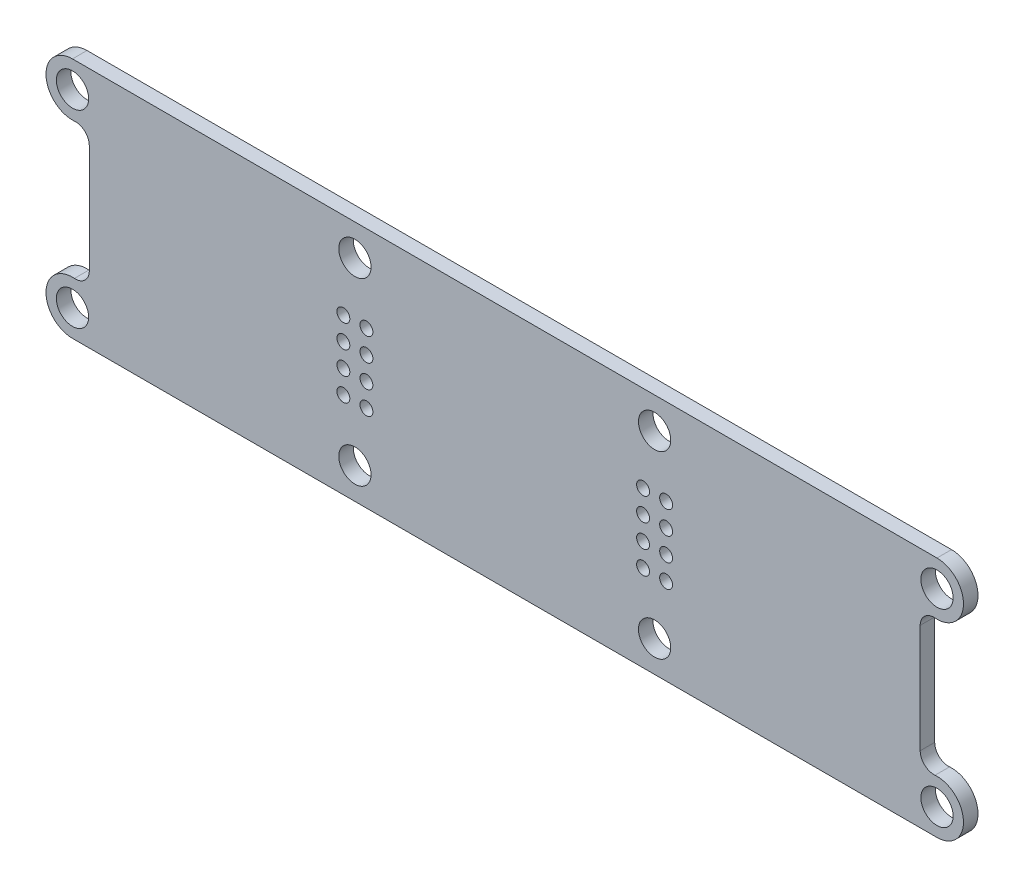
SolidWorks part; units mm, degrees
ref_plane "Front Plane" through (0, 0, 0) normal (0, 0, 1) x (1, 0, 0)
ref_plane "Top Plane" through (0, 0, 0) normal (0, 1, 0) x (1, 0, 0)
ref_plane "Right Plane" through (0, 0, 0) normal (1, 0, 0) x (0, 0, -1)
sketch "Sketch1" plane through (0, 0, -38.7925) normal (0, 0, -1) x (-1, 0, 0)
  line L72 (23.8125, 6.6675) -> (-23.8125, 6.6675)
  line L74 (-23.8125, -6.6675) -> (23.8125, -6.6675)
  line L75 (22.887, -2.9905) -> (22.887, 2.9905)
  line L76 (23.8125, 6.6675) -> (-23.8125, 6.6675)
  line L78 (-23.8125, -6.6675) -> (23.8125, -6.6675)
  line L152 (-22.887, 2.9905) -> (-22.887, -2.9905)
  line L153 (-22.887, 2.9905) -> (-22.887, -2.9905)
  line L164 (22.887, -2.9905) -> (22.887, 2.9905)
  arc A78 (23.7051, 3.7505) -> (23.8125, 6.6675) centre (23.8125, 5.207) ccw
  arc A79 (-23.8125, 6.6675) -> (-23.7051, 3.7505) centre (-23.8125, 5.207) ccw
  arc A80 (-23.7051, -3.7505) -> (-23.8125, -6.6675) centre (-23.8125, -5.207) ccw
  arc A81 (23.8125, -6.6675) -> (23.7051, -3.7505) centre (23.8125, -5.207) ccw
  arc A82 (23.7051, 3.7505) -> (23.8125, 6.6675) centre (23.8125, 5.207) ccw
  arc A83 (-23.8125, 6.6675) -> (-23.7051, 3.7505) centre (-23.8125, 5.207) ccw
  arc A84 (-23.7051, -3.7505) -> (-23.8125, -6.6675) centre (-23.8125, -5.207) ccw
  arc A85 (23.8125, -6.6675) -> (23.7051, -3.7505) centre (23.8125, -5.207) ccw
  arc A173 (-22.887, 2.9905) -> (-23.7051, 3.7505) centre (-23.649, 2.9905) ccw
  arc A174 (-22.887, 2.9905) -> (-23.7051, 3.7505) centre (-23.649, 2.9905) ccw
  arc A175 (-23.7051, -3.7505) -> (-22.887, -2.9905) centre (-23.649, -2.9905) ccw
  arc A176 (-23.7051, -3.7505) -> (-22.887, -2.9905) centre (-23.649, -2.9905) ccw
  arc A195 (23.7051, 3.7505) -> (22.887, 2.9905) centre (23.649, 2.9905) ccw
  arc A196 (23.7051, 3.7505) -> (22.887, 2.9905) centre (23.649, 2.9905) ccw
  arc A197 (22.887, -2.9905) -> (23.7051, -3.7505) centre (23.649, -2.9905) ccw
  arc A198 (22.887, -2.9905) -> (23.7051, -3.7505) centre (23.649, -2.9905) ccw
  dimension "D1" = 0.127
extrude "Boss-Extrude1" add sketch "Sketch1" along normal blind 0.8
sketch "Sketch2" plane through (0, 0, -39.5925) normal (0, 0, -1) x (-1, 0, 0)
  circle A13 centre (-7.62, -1.905) radius 0.3556
  circle A17 centre (-7.62, -1.905) radius 0.3556
  circle A23 centre (-8.89, -1.905) radius 0.3556
  circle A37 centre (-8.89, -1.905) radius 0.3556
  circle A39 centre (-7.62, 1.905) radius 0.3556
  circle A41 centre (-7.62, 1.905) radius 0.3556
  circle A43 centre (-8.89, 1.905) radius 0.3556
  circle A45 centre (-8.89, 1.905) radius 0.3556
  circle A47 centre (-7.62, 0.635) radius 0.3556
  circle A49 centre (-7.62, 0.635) radius 0.3556
  circle A51 centre (-8.89, 0.635) radius 0.3556
  circle A53 centre (-8.89, 0.635) radius 0.3556
  circle A55 centre (-7.62, -0.635) radius 0.3556
  circle A226 centre (-7.62, -0.635) radius 0.3556
  circle A227 centre (-8.89, -0.635) radius 0.3556
  circle A228 centre (-8.89, -0.635) radius 0.3556
  circle A247 centre (8.89, 1.905) radius 0.3556
  circle A248 centre (8.89, 1.905) radius 0.3556
  circle A249 centre (7.62, 1.905) radius 0.3556
  circle A250 centre (7.62, 1.905) radius 0.3556
  circle A263 centre (8.89, -1.905) radius 0.3556
  circle A264 centre (8.89, -1.905) radius 0.3556
  circle A265 centre (7.62, -1.905) radius 0.3556
  circle A266 centre (7.62, -1.905) radius 0.3556
  circle A267 centre (8.89, -0.635) radius 0.3556
  circle A268 centre (8.89, -0.635) radius 0.3556
  circle A269 centre (7.62, -0.635) radius 0.3556
  circle A270 centre (7.62, -0.635) radius 0.3556
  circle A271 centre (8.89, 0.635) radius 0.3556
  circle A272 centre (8.89, 0.635) radius 0.3556
  circle A273 centre (7.62, 0.635) radius 0.3556
  circle A274 centre (7.62, 0.635) radius 0.3556
  dimension "D5" = 0
  dimension "D9" = 0
  dimension "D10" = 0
  dimension "D11" = 0
  dimension "D12" = 0
  dimension "D19" = 0
  dimension "D20" = 0
  dimension "D21" = 0
  dimension "D31" = 0
  dimension "D32" = 0
  dimension "D39" = 0
  dimension "D40" = 0
  dimension "D41" = 0
  dimension "D42" = 0
  dimension "D43" = 0
  dimension "D44" = 0
extrude "Cut-Extrude1" cut sketch "Sketch2" against normal through all
sketch "Sketch3" plane through (0, 0, -39.5925) normal (0, 0, -1) x (-1, 0, 0)
  circle A0 centre (-23.8125, 5.207) radius 0.889
  circle A1 centre (-23.8125, -5.207) radius 0.889
  circle A2 centre (23.8125, 5.207) radius 0.889
  circle A3 centre (23.8125, -5.207) radius 0.889
  circle A4 centre (-8.255, 4.953) radius 0.889
  circle A5 centre (8.255, 4.953) radius 0.889
  circle A6 centre (8.255, -4.953) radius 0.889
  circle A7 centre (-8.255, -4.953) radius 0.889
  dimension "D1" = 1.778
  dimension "D2" = 47.625
  dimension "D3" = 10.414
extrude "Cut-Extrude2" cut sketch "Sketch3" against normal through all both and the other way through all
sketch "Sketch4" plane through (0, 0, -39.5925) normal (0, 0, -1) x (-1, 0, 0)
  line L0 (-23.8125, -6.6675) -> (-23.8125, -5.207) construction
  line L1 (-23.8125, -5.207) -> (-23.7051, -3.7505) construction
  line L2 (-23.7051, -3.7505) -> (-23.649, -2.9905) construction
  line L3 (-23.649, -2.9905) -> (-22.887, -2.9905) construction
  line L4 (-22.887, 2.9905) -> (-22.887, -2.9905)
  line L5 (-23.8125, -6.6675) -> (23.8125, -6.6675)
  line L6 (22.887, -2.9905) -> (22.887, 2.9905)
  line L7 (23.8125, 6.6675) -> (-23.8125, 6.6675)
  line L8 (-22.887, 2.9905) -> (-22.887, -2.9905)
  line L9 (-23.8125, -6.6675) -> (23.8125, -6.6675)
  line L10 (22.887, -2.9905) -> (22.887, 2.9905)
  line L11 (23.8125, 6.6675) -> (-23.8125, 6.6675)
  arc A8 (-22.887, 2.9905) -> (-23.7051, 3.7505) centre (-23.649, 2.9905) ccw
  arc A9 (-23.7051, -3.7505) -> (-22.887, -2.9905) centre (-23.649, -2.9905) ccw
  arc A10 (-23.7051, -3.7505) -> (-23.8125, -6.6675) centre (-23.8125, -5.207) ccw
  arc A11 (23.8125, -6.6675) -> (23.7051, -3.7505) centre (23.8125, -5.207) ccw
  arc A12 (22.887, -2.9905) -> (23.7051, -3.7505) centre (23.649, -2.9905) ccw
  arc A13 (23.7051, 3.7505) -> (22.887, 2.9905) centre (23.649, 2.9905) ccw
  arc A14 (23.7051, 3.7505) -> (23.8125, 6.6675) centre (23.8125, 5.207) ccw
  arc A15 (-23.8125, 6.6675) -> (-23.7051, 3.7505) centre (-23.8125, 5.207) ccw
  arc A16 (-22.887, 2.9905) -> (-23.7051, 3.7505) centre (-23.649, 2.9905) ccw
  arc A17 (-23.7051, -3.7505) -> (-22.887, -2.9905) centre (-23.649, -2.9905) ccw
  arc A18 (-23.7051, -3.7505) -> (-23.8125, -6.6675) centre (-23.8125, -5.207) ccw
  arc A19 (23.8125, -6.6675) -> (23.7051, -3.7505) centre (23.8125, -5.207) ccw
  arc A20 (22.887, -2.9905) -> (23.7051, -3.7505) centre (23.649, -2.9905) ccw
  arc A21 (23.7051, 3.7505) -> (22.887, 2.9905) centre (23.649, 2.9905) ccw
  arc A22 (23.7051, 3.7505) -> (23.8125, 6.6675) centre (23.8125, 5.207) ccw
  arc A23 (-23.8125, 6.6675) -> (-23.7051, 3.7505) centre (-23.8125, 5.207) ccw
  point P8 (8.89, -1.905)
  point P13 (-25.272, -5.1532)
  point P16 (-7.62, -1.905)
  point P21 (25.272, -5.1532)
  point P24 (25.272, -6.6675)
  point P25 (25.272, -5.1532)
  point P27 (-8.255, -4.953)
  dimension "D4" = 50.544
  dimension "D2" = 184.219
  dimension "D3" = 94.219
  dimension "D1" = 0
ref_plane "Plane1" through (7.62, 0, 0) normal (1, 0, 0) x (0, 0, -1)
